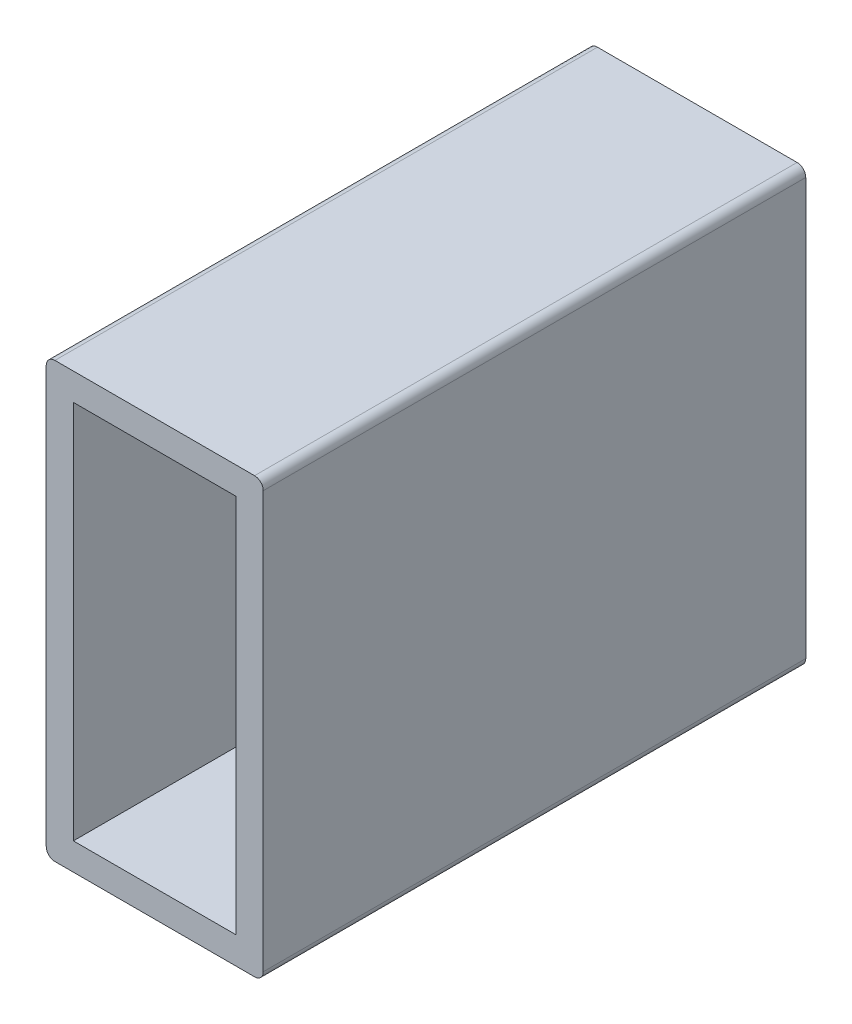
SolidWorks part; units mm, degrees
ref_plane "Front Plane" through (0, 0, 0) normal (0, 0, 1) x (1, 0, 0)
ref_plane "Top Plane" through (0, 0, 0) normal (0, 1, 0) x (1, 0, 0)
ref_plane "Right Plane" through (0, 0, 0) normal (1, 0, 0) x (0, 0, -1)
sketch "Sketch1" plane through (0, 0, 0) normal (0, 0, 1) x (1, 0, 0)
  line L0 (-9.525, 22.225) -> (9.525, 22.225)
  line L1 (-11.684, -25.4) -> (11.684, -25.4)
  line L2 (-12.7, -24.384) -> (-12.7, 24.384)
  line L3 (-11.684, 25.4) -> (11.684, 25.4)
  line L4 (12.7, -24.384) -> (12.7, 24.384)
  line L5 (-12.7, -25.4) -> (12.7, 25.4) construction
  line L6 (-12.7, 25.4) -> (12.7, -25.4) construction
  line L7 (9.525, -22.225) -> (9.525, 22.225)
  line L8 (-9.525, -22.225) -> (9.525, -22.225)
  line L9 (-9.525, -22.225) -> (-9.525, 22.225)
  arc A0 (-12.7, -24.384) -> (-11.684, -25.4) centre (-11.684, -24.384) ccw
  arc A1 (11.684, -25.4) -> (12.7, -24.384) centre (11.684, -24.384) ccw
  arc A2 (12.7, 24.384) -> (11.684, 25.4) centre (11.684, 24.384) ccw
  arc A3 (-11.684, 25.4) -> (-12.7, 24.384) centre (-11.684, 24.384) ccw
  arc A4 (9.525, 22.225) -> (9.525, 22.225) centre (9.525, 22.225) ccw
  arc A5 (9.525, -22.225) -> (9.525, -22.225) centre (9.525, -22.225) ccw
  arc A6 (-9.525, -22.225) -> (-9.525, -22.225) centre (-9.525, -22.225) ccw
  arc A7 (-9.525, 22.225) -> (-9.525, 22.225) centre (-9.525, 22.225) ccw
  point P0 (0, 0)
  dimension "D3" = 1.016
  dimension "D1" = 25.4
  dimension "D2" = 50.8
  dimension "D4" = 3.175
extrude "Boss-Extrude1" add sketch "Sketch1" along normal mid plane 63.5
